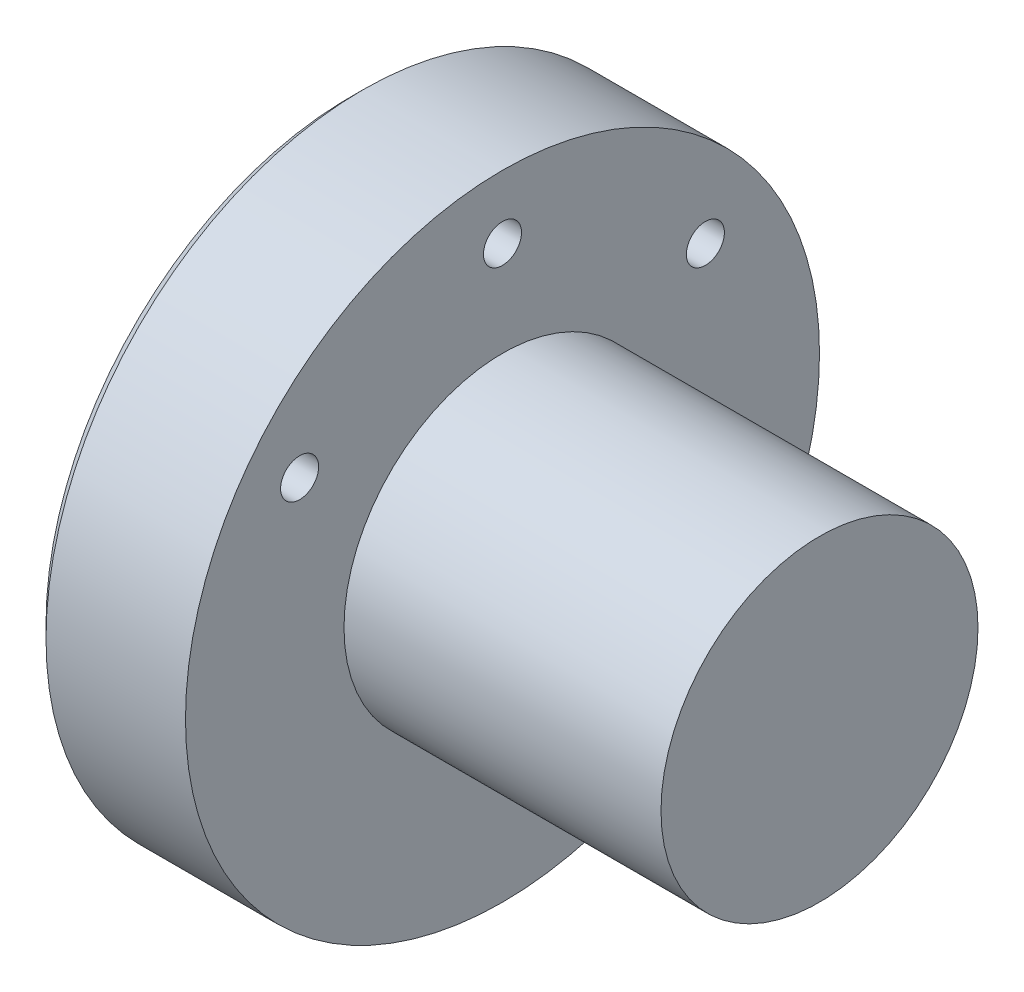
SolidWorks part; units mm, degrees
ref_plane "Front Plane" through (0, 0, 0) normal (0, 0, 1) x (1, 0, 0)
ref_plane "Top Plane" through (0, 0, 0) normal (0, 1, 0) x (1, 0, 0)
ref_plane "Right Plane" through (0, 0, 0) normal (1, 0, 0) x (0, 0, -1)
sketch "Sketch1" plane through (0, 0, 0) normal (0, 0, 1) x (1, 0, 0)
  line L0 (0, 0) -> (40, 0)
  line L1 (40, 0) -> (40, 12.5)
  line L2 (40, 12.5) -> (15, 12.5)
  line L3 (15, 12.5) -> (15, 25)
  line L4 (15, 25) -> (3, 25)
  line L5 (3, 25) -> (3, 6)
  line L6 (3, 6) -> (0, 6)
  line L7 (0, 6) -> (0, 0)
  dimension "D1" = 12
  dimension "D2" = 40
  dimension "D3" = 25
  dimension "D4" = 12.5
  dimension "D5" = 25
  dimension "D6" = 6
revolve "Revolve1" add sketch "Sketch1" angle 360 about L0
chamfer "Chamfer1" distance 1 angle 45 2 edges at (3, 0, 25) (0, 0, 6)
sketch "Sketch2" plane through (3, 0, 0) normal (-1, 0, 0) x (0, 0, 1)
  line L0 (0, 0) -> (9.4804, 0) construction
  circle A0 centre (-16, 12) radius 1.5
  circle A1 centre (0, 20) radius 1.5
  circle A2 centre (16, 12) radius 1.5
  circle A3 centre (0, 0) radius 20 construction
  point P9 (0, 0)
  point P10 (17.447, 9.7776)
  dimension "D2" = 40
  dimension "D3" = 3
  dimension "D1" = 12
extrude "Cut-Extrude1" cut sketch "Sketch2" against normal through all
chamfer "Chamfer2" distance 0.5 angle 45 3 edges at (3, 12, 17.5) (3, 20, 1.5) (3, 12, -14.5)
